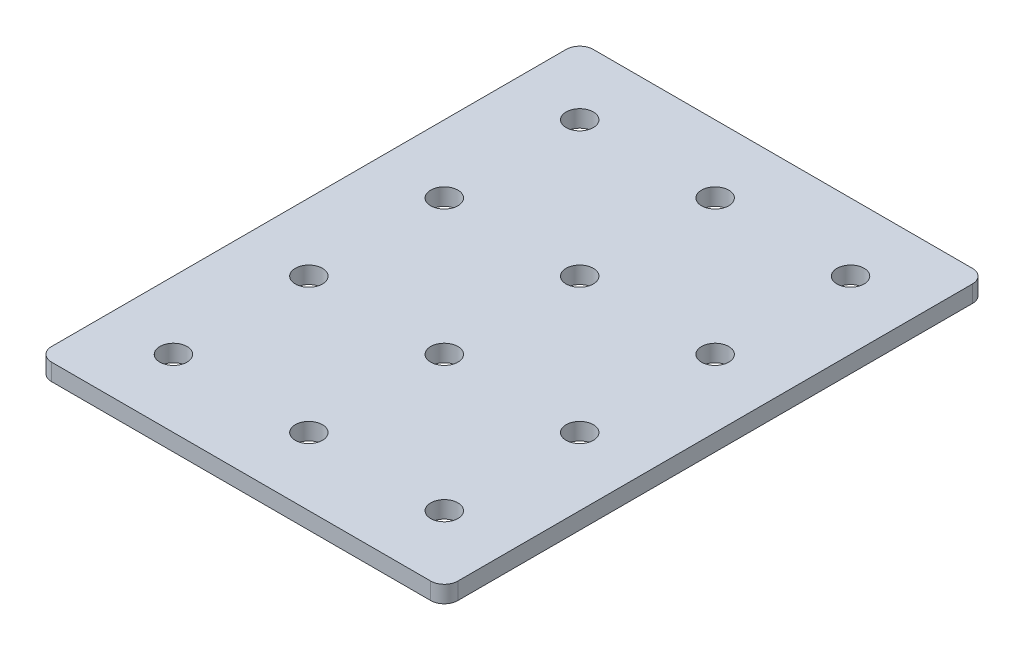
SolidWorks part; units mm, degrees
ref_plane "Front Plane" through (0, 0, 0) normal (0, 0, 1) x (1, 0, 0)
ref_plane "Top Plane" through (0, 0, 0) normal (0, 1, 0) x (1, 0, 0)
ref_plane "Right Plane" through (0, 0, 0) normal (1, 0, 0) x (0, 0, -1)
sketch "Sketch1" plane through (0, 0, 0) normal (0, 1, 0) x (1, 0, 0)
  line L1 (-38.1, -50.8) -> (38.1, -50.8)
  line L2 (-38.1, -50.8) -> (-38.1, 50.8)
  line L3 (-38.1, 50.8) -> (38.1, 50.8)
  line L4 (38.1, -50.8) -> (38.1, 50.8)
  line L5 (-38.1, -50.8) -> (38.1, 50.8) construction
  line L6 (-38.1, 50.8) -> (38.1, -50.8) construction
  point P0 (0, 0)
  dimension "D1" = 76.2
  dimension "D2" = 101.6
extrude "Boss-Extrude1" add sketch "Sketch1" along normal blind 3.175
sketch "Sketch2" plane through (0, 3.175, 0) normal (0, 1, 0) x (1, 0, 0)
  line L0 (-38.1, -50.8) -> (38.1, -50.8) construction
  line L1 (-38.1, 50.8) -> (-38.1, -50.8) construction
  circle A0 centre (-25.4, -38.1) radius 2.5527
  dimension "D1" = 5.1054
  dimension "D2" = 12.7
  dimension "D3" = 12.7
extrude "Cut-Extrude1" cut sketch "Sketch2" against normal blind 3.175
pattern_linear "LPattern1" count 4 spacing 25.4 along (0, 0, -1) count 3 spacing 25.4 along (1, 0, 0) of "Cut-Extrude1"
fillet "Fillet1" radius 2.54 4 edges at (-38.1, 1.5875, 50.8) (38.1, 1.5875, 50.8) (38.1, 1.5875, -50.8) (-38.1, 1.5875, -50.8)
